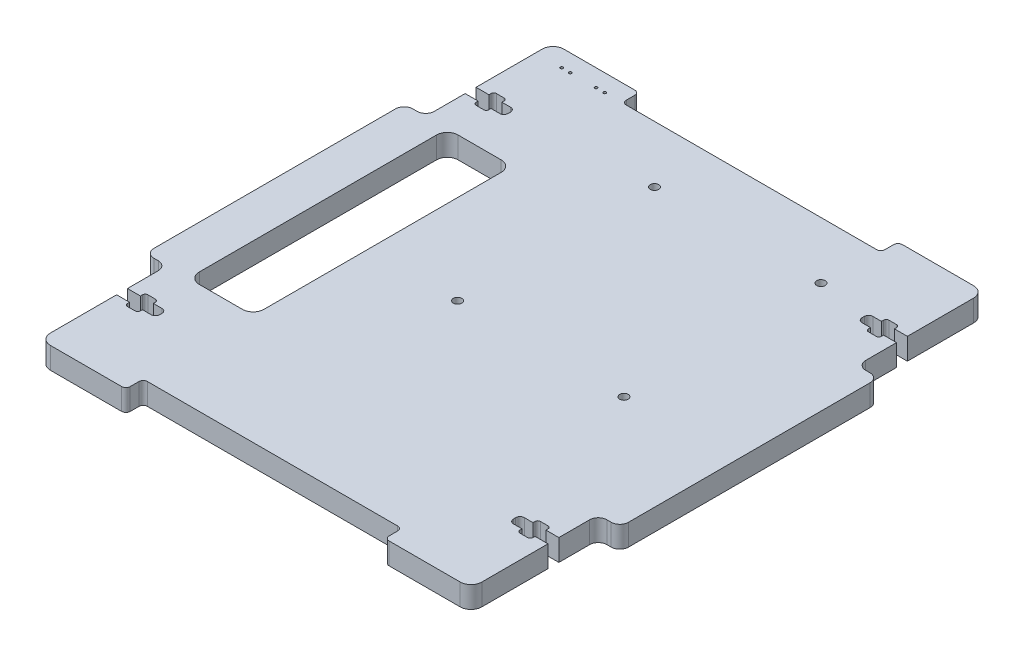
SolidWorks part; units mm, degrees
ref_plane "Front Plane" through (0, 0, 0) normal (0, 0, 1) x (1, 0, 0)
ref_plane "Top Plane" through (0, 0, 0) normal (0, 1, 0) x (1, 0, 0)
ref_plane "Right Plane" through (0, 0, 0) normal (1, 0, 0) x (0, 0, -1)
sketch "Sketch1" plane through (0, 0, 0) normal (0, 1, 0) x (1, 0, 0)
  line L0 (0, 107.7058) -> (0, -133.9423) construction
  line L1 (-60.325, -75.565) -> (-39.37, -75.565)
  line L2 (-63.5, -72.39) -> (-63.5, -40.64)
  line L3 (-60.325, 75.565) -> (-39.37, 75.565)
  line L4 (63.5, -72.39) -> (63.5, -40.64)
  line L5 (-63.5, -75.565) -> (63.5, 75.565) construction
  line L6 (-63.5, 75.565) -> (63.5, -75.565) construction
  line L7 (-112.9847, 0) -> (99.1491, 0) construction
  line L8 (66.04, -38.1) -> (67.31, -38.1)
  line L11 (66.04, 38.1) -> (67.31, 38.1)
  line L12 (69.85, -35.56) -> (69.85, 35.56)
  line L14 (-66.04, 38.1) -> (-67.31, 38.1)
  line L15 (-69.85, -35.56) -> (-69.85, 35.56)
  line L16 (-66.04, -38.1) -> (-67.31, -38.1)
  line L17 (63.5, 40.64) -> (63.5, 72.39)
  line L18 (-63.5, 40.64) -> (-63.5, 72.39)
  line L19 (38.1, 74.295) -> (38.1, 71.755)
  line L22 (36.83, 70.485) -> (-36.83, 70.485)
  line L23 (-38.1, 74.295) -> (-38.1, 71.755)
  line L24 (39.37, 75.565) -> (60.325, 75.565)
  line L25 (-38.1, -74.295) -> (-38.1, -71.755)
  line L26 (38.1, -74.295) -> (38.1, -71.755)
  line L27 (36.83, -70.485) -> (-36.83, -70.485)
  line L28 (39.37, -75.565) -> (60.325, -75.565)
  line L29 (-53.975, -38.1) -> (-41.275, -38.1)
  line L31 (-57.15, -34.925) -> (-57.15, 34.925)
  line L32 (-53.975, 38.1) -> (-41.275, 38.1)
  line L33 (-38.1, -34.925) -> (-38.1, 34.925)
  line L38 (-29.21, -43.18) -> (57.15, 43.18) construction
  line L39 (-29.21, 43.18) -> (57.15, -43.18) construction
  line L44 (-84.4787, 70.485) -> (-10.8178, 70.485) construction
  line L45 (-44.45, 73.66) -> (-44.45, 66.8374) construction
  line L46 (-49.53, 78.7562) -> (-49.53, 65.1476) construction
  line L47 (-54.61, 73.66) -> (-54.61, 66.8374) construction
  arc A0 (-60.325, -75.565) -> (-63.5, -72.39) centre (-60.325, -72.39) cw
  arc A1 (60.325, -75.565) -> (63.5, -72.39) centre (60.325, -72.39) ccw
  arc A2 (60.325, 75.565) -> (63.5, 72.39) centre (60.325, 72.39) cw
  arc A3 (-63.5, 72.39) -> (-60.325, 75.565) centre (-60.325, 72.39) cw
  arc A4 (63.5, 40.64) -> (66.04, 38.1) centre (66.04, 40.64) ccw
  arc A5 (67.31, 38.1) -> (69.85, 35.56) centre (67.31, 35.56) cw
  arc A6 (67.31, -38.1) -> (69.85, -35.56) centre (67.31, -35.56) ccw
  arc A7 (66.04, -38.1) -> (63.5, -40.64) centre (66.04, -40.64) ccw
  arc A8 (-63.5, -40.64) -> (-66.04, -38.1) centre (-66.04, -40.64) ccw
  arc A9 (-69.85, -35.56) -> (-67.31, -38.1) centre (-67.31, -35.56) ccw
  arc A10 (-67.31, 38.1) -> (-69.85, 35.56) centre (-67.31, 35.56) ccw
  arc A11 (-63.5, 40.64) -> (-66.04, 38.1) centre (-66.04, 40.64) cw
  arc A12 (38.1, 74.295) -> (39.37, 75.565) centre (39.37, 74.295) cw
  arc A13 (38.1, 71.755) -> (36.83, 70.485) centre (36.83, 71.755) cw
  arc A14 (-36.83, 70.485) -> (-38.1, 71.755) centre (-36.83, 71.755) cw
  arc A15 (-39.37, 75.565) -> (-38.1, 74.295) centre (-39.37, 74.295) cw
  arc A16 (-39.37, -75.565) -> (-38.1, -74.295) centre (-39.37, -74.295) ccw
  arc A17 (-36.83, -70.485) -> (-38.1, -71.755) centre (-36.83, -71.755) ccw
  arc A18 (38.1, -71.755) -> (36.83, -70.485) centre (36.83, -71.755) ccw
  arc A19 (38.1, -74.295) -> (39.37, -75.565) centre (39.37, -74.295) ccw
  arc A20 (-41.275, -38.1) -> (-38.1, -34.925) centre (-41.275, -34.925) ccw
  arc A21 (-53.975, -38.1) -> (-57.15, -34.925) centre (-53.975, -34.925) cw
  arc A22 (-57.15, 34.925) -> (-53.975, 38.1) centre (-53.975, 34.925) cw
  arc A23 (-41.275, 38.1) -> (-38.1, 34.925) centre (-41.275, 34.925) cw
  circle A28 centre (-44.45, 70.485) radius 2.54
  circle A29 centre (-45.72, 70.485) radius 0.4
  circle A30 centre (-43.18, 70.485) radius 0.4
  circle A31 centre (-55.88, 70.485) radius 0.4
  circle A32 centre (-53.34, 70.485) radius 0.4
  circle A33 centre (-54.61, 70.485) radius 2.54
  point P0 (0, 0)
  point P32 (63.5, 38.1)
  point P35 (69.85, 38.1)
  point P38 (69.85, -38.1)
  point P41 (63.5, -38.1)
  point P44 (-63.5, -38.1)
  point P47 (-69.85, -38.1)
  point P50 (-69.85, 38.1)
  point P53 (-63.5, 38.1)
  point P60 (38.1, 75.565)
  point P63 (38.1, 70.485)
  point P66 (-38.1, 70.485)
  point P69 (-38.1, 75.565)
  point P82 (-38.1, -75.565)
  point P83 (-38.1, -70.485)
  point P84 (38.1, -70.485)
  point P85 (38.1, -75.565)
  point P90 (0, 0)
  point P99 (-38.1, -38.1)
  point P102 (-57.15, -38.1)
  point P105 (-57.15, 38.1)
  point P108 (-38.1, 38.1)
  dimension "D5" = 3.175
  dimension "D6" = 2.54
  dimension "D9" = 1.27
  dimension "D14" = 3.175
  dimension "D11" = 5.08
  dimension "D15" = 0.8
  dimension "D1" = 151.13
  dimension "D2" = 127
  dimension "D3" = 6.35
  dimension "D4" = 76.2
  dimension "D7" = 76.2
  dimension "D8" = 5.08
  dimension "D10" = 76.2
  dimension "D12" = 25.4
  dimension "D13" = 19.05
  dimension "D16" = 6.35
  dimension "D17" = 1.27
  dimension "D18" = 5.08
  dimension "D19" = 86.36
  dimension "D20" = 12.7
extrude "Boss-Extrude1" add sketch "Sketch1" against normal blind 6.35
sketch "Sketch2" plane through (63.5, 0, 0) normal (1, 0, 0) x (0, 0, -1)
  line L0 (0, 19.0868) -> (0, -36.5366) construction
  line L1 (-72.39, 0) -> (-40.64, 0) construction
  line L2 (-52.908, 0) -> (-49.708, 0)
  line L3 (-52.908, 0) -> (-52.908, -6.35)
  line L4 (-72.39, -6.35) -> (-40.64, -6.35) construction
  line L5 (-49.708, 0) -> (-49.708, -6.35)
  line L6 (49.708, 0) -> (49.708, -6.35)
  line L7 (40.64, 0) -> (72.39, 0) construction
  line L8 (40.64, -6.35) -> (72.39, -6.35) construction
  line L9 (52.908, 0) -> (52.908, -6.35)
  line L10 (-49.708, -6.35) -> (-52.908, -6.35)
  line L11 (49.708, 0) -> (52.908, 0)
  line L12 (52.908, -6.35) -> (49.708, -6.35)
  point P4 (0, 0)
  dimension "D1" = 52.908
  dimension "D2" = 49.708
  dimension "D3" = 49.708
  dimension "D4" = 52.908
sketch "Sketch4" plane through (-63.5, 0, 0) normal (-1, 0, 0) x (0, 0, 1)
  line L0 (-52.908, 0) -> (-49.708, 0)
  line L1 (-52.908, 0) -> (-52.908, -6.35)
  line L2 (-40.64, 0) -> (-72.39, 0) construction
  line L3 (-40.64, -6.35) -> (-72.39, -6.35) construction
  line L4 (-49.708, 0) -> (-49.708, -6.35)
  line L5 (-49.708, -6.35) -> (-52.908, -6.35)
  line L6 (49.708, 0) -> (49.708, -6.35)
  line L7 (72.39, 0) -> (40.64, 0) construction
  line L8 (72.39, -6.35) -> (40.64, -6.35) construction
  line L9 (52.908, 0) -> (52.908, -6.35)
  line L10 (0, 13.7207) -> (0, -24.8398) construction
  line L11 (49.708, 0) -> (52.908, 0)
  line L12 (52.908, -6.35) -> (49.708, -6.35)
  dimension "D1" = 52.908
  dimension "D2" = 49.708
  dimension "D3" = 49.708
  dimension "D4" = 52.908
sketch "Sketch5" plane through (0, 0, 0) normal (0, 1, 0) x (1, 0, 0)
  line L1 (37.2, -4.235) -> (37.2, 53.765) construction
  line L2 (37.2, -4.235) -> (-11.8, -4.235) construction
  line L3 (-11.8, -4.235) -> (-11.8, 53.765) construction
  line L4 (37.2, 53.765) -> (-11.8, 53.765) construction
  line L5 (37.2, -4.235) -> (-11.8, 53.765) construction
  line L6 (-11.8, -4.235) -> (37.2, 53.765) construction
  line L7 (69.85, -35.56) -> (69.85, 35.56) construction
  line L8 (-60.325, 75.565) -> (-39.37, 75.565) construction
  circle A0 centre (-11.8, -4.235) radius 1.25
  circle A1 centre (-11.8, 53.765) radius 1.25
  circle A2 centre (37.2, -4.235) radius 1.25
  circle A3 centre (37.2, 53.765) radius 1.25
  point P0 (12.7, 24.765)
  dimension "D5" = 2.5
  dimension "D1" = 58
  dimension "D2" = 49
  dimension "D3" = 57.15
  dimension "D4" = 50.8
extrude "Cut-Extrude3" cut sketch "Sketch5" against normal up to surface (6.35 mm away) contours A0 | A1 | A3 | A2 up to face at (0, -6.35, 0)
extrude "Cut-Extrude4" cut sketch "Sketch4" against normal blind 11.43 contours L12 L9 L11 L6 | L1 L5 L4 L0
extrude "Cut-Extrude5" cut sketch "Sketch2" against normal blind 11.43 contours L12 L9 L11 L6 | L5 L10 L3 L2
fillet "Fillet1" radius 1.27 8 edges at (-52.07, -3.175, 52.908) (-52.07, -3.175, 49.708) (52.07, -3.175, 52.908) (52.07, -3.175, 49.708) (52.07, -3.175, -49.708) (52.07, -3.175, -52.908) (-52.07, -3.175, -49.708) (-52.07, -3.175, -52.908)
sketch "Sketch6" plane through (0, 0, 0) normal (0, 1, 0) x (1, 0, 0)
  line L0 (-52.07, 51.638) -> (-52.07, 50.978) construction
  line L1 (-65.3927, 51.308) -> (74.6098, 51.308) construction
  line L2 (-63.5, 52.908) -> (-63.5, 72.39) construction
  line L3 (-59.69, 48.308) -> (-55.88, 48.308)
  line L4 (-59.69, 48.308) -> (-59.69, 54.308)
  line L5 (-59.69, 54.308) -> (-55.88, 54.308)
  line L6 (-55.88, 48.308) -> (-55.88, 54.308)
  line L7 (-59.69, 48.308) -> (-55.88, 54.308) construction
  line L8 (-59.69, 54.308) -> (-55.88, 48.308) construction
  line L9 (-107.3507, 0) -> (141.7236, 0) construction
  line L10 (0, 100.6023) -> (0, -92.6846) construction
  line L11 (59.69, 54.308) -> (55.88, 54.308)
  line L12 (55.88, 48.308) -> (55.88, 54.308)
  line L13 (59.69, 48.308) -> (55.88, 48.308)
  line L14 (59.69, 48.308) -> (59.69, 54.308)
  line L15 (59.69, -48.308) -> (59.69, -54.308)
  line L16 (59.69, -48.308) -> (55.88, -48.308)
  line L17 (55.88, -48.308) -> (55.88, -54.308)
  line L18 (59.69, -54.308) -> (55.88, -54.308)
  line L19 (-59.69, -54.308) -> (-55.88, -54.308)
  line L20 (-55.88, -48.308) -> (-55.88, -54.308)
  line L21 (-59.69, -48.308) -> (-55.88, -48.308)
  line L22 (-59.69, -48.308) -> (-59.69, -54.308)
  point P0 (-52.07, 51.308)
  point P5 (-57.785, 51.308)
  point P29 (-59.69, 51.308)
  dimension "D1" = 6
  dimension "D2" = 3.81
  dimension "D3" = 3.81
extrude "Cut-Extrude6" cut sketch "Sketch6" against normal up to surface (6.35 mm away) contours L18 L15 L16 L17 | L21 L22 L19 L20 | L3 L6 L5 L4 | L13 L12 L11 L14 up to face at (0, -6.35, 0)
fillet "Fillet2" radius 0.762 16 edges at (-59.69, -3.175, 54.308) (-55.88, -3.175, 54.308) (-59.69, -3.175, 48.308) (-55.88, -3.175, 48.308) (55.88, -3.175, 54.308) (59.69, -3.175, 54.308) (55.88, -3.175, 48.308) (59.69, -3.175, 48.308) (55.88, -3.175, -48.308) (59.69, -3.175, -48.308) (55.88, -3.175, -54.308) (59.69, -3.175, -54.308) (-59.69, -3.175, -48.308) (-55.88, -3.175, -48.308) (-59.69, -3.175, -54.308) (-55.88, -3.175, -54.308)
